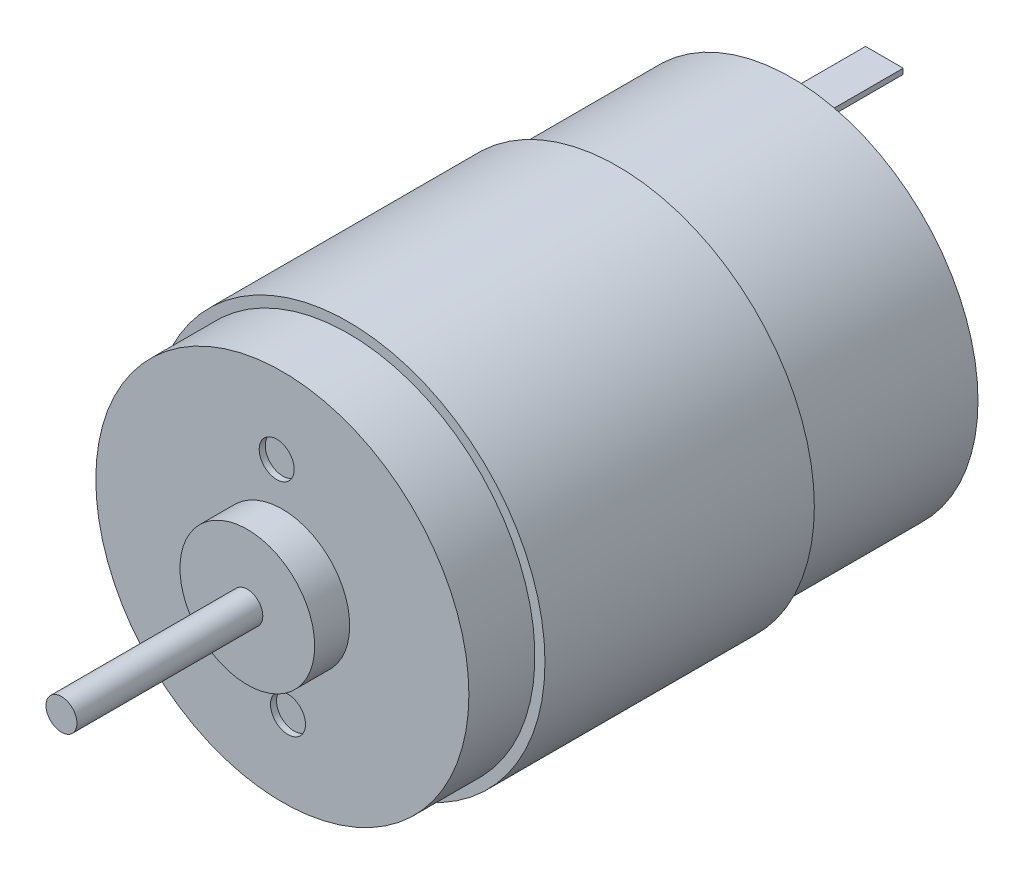
SolidWorks part; units mm, degrees
ref_plane "正面" through (0, 0, 0) normal (0, 0, 1) x (1, 0, 0)
ref_plane "平面" through (0, 0, 0) normal (0, 1, 0) x (1, 0, 0)
ref_plane "右側面" through (0, 0, 0) normal (1, 0, 0) x (0, 0, -1)
sketch "ｽｹｯﾁ1" plane through (0, 0, 0) normal (0, 0, 1) x (1, 0, 0)
  circle A0 centre (0, 0) radius 13.85
  dimension "D1" = 27.7
extrude "ﾎﾞｽ - 押し出し1" add sketch "ｽｹｯﾁ1" along normal blind 37.8
sketch "ｽｹｯﾁ2" plane through (0, 0, 37.8) normal (0, 0, 1) x (1, 0, 0)
  circle A0 centre (0, 0) radius 5
  dimension "D1" = 10
extrude "ﾎﾞｽ - 押し出し2" add sketch "ｽｹｯﾁ2" along normal blind 2.6
sketch "ｽｹｯﾁ3" plane through (0, 0, 40.4) normal (0, 0, 1) x (1, 0, 0)
  circle A0 centre (0, 0) radius 1.15
  dimension "D1" = 2.3
extrude "ﾎﾞｽ - 押し出し3" add sketch "ｽｹｯﾁ3" along normal blind 16.4 from surface at -2.6 starting at face at (5, 0, 37.8)
sketch "ｽｹｯﾁ4" plane through (0, 0, 0) normal (0, 0, -1) x (-1, 0, 0)
  circle A0 centre (0, 0) radius 14.6
  dimension "D1" = 29.2
extrude "ﾎﾞｽ - 押し出し4" add sketch "ｽｹｯﾁ4" along normal blind 20 from offset 32.9 offset against normal yes
sketch "ｽｹｯﾁ5" plane through (0, 0, 0) normal (0, 0, -1) x (-1, 0, 0)
  circle A0 centre (0, 0) radius 5
  point P2 (0, 0)
  dimension "D1" = 10
extrude "ﾎﾞｽ - 押し出し5" add sketch "ｽｹｯﾁ5" along normal blind 2.6
sketch "ｽｹｯﾁ6" plane through (0, 0, 0) normal (0, 0, -1) x (-1, 0, 0)
  line L0 (-7.9588, 0) -> (7.9588, 0) construction
  line L1 (-1.4, 11.7) -> (1.4, 11.7)
  line L2 (-1.4, 11.7) -> (-1.4, 11.3)
  line L3 (-1.4, 11.3) -> (1.4, 11.3)
  line L4 (1.4, 11.7) -> (1.4, 11.3)
  line L5 (-1.4, 11.7) -> (1.4, 11.3) construction
  line L6 (-1.4, 11.3) -> (1.4, 11.7) construction
  line L7 (-1.4, -11.3) -> (1.4, -11.3)
  line L8 (1.4, -11.7) -> (1.4, -11.3)
  line L9 (-1.4, -11.7) -> (1.4, -11.7)
  line L10 (-1.4, -11.7) -> (-1.4, -11.3)
  point P4 (0, 11.5)
  point P5 (0, 0)
  dimension "D1" = 2.8
  dimension "D2" = 0.4
  dimension "D3" = 22.6
extrude "ﾎﾞｽ - 押し出し6" add sketch "ｽｹｯﾁ6" along normal blind 6.9
sketch "ｽｹｯﾁ7" plane through (0, 0, 37.8) normal (0, 0, 1) x (1, 0, 0)
  line L0 (-10.1434, -0.5316) -> (20.731, 1.0865) construction
  line L1 (-0.834, 15.9137) -> (0.869, -16.5818) construction
  line L2 (0, 15.8662) -> (0, -16.6076) construction
  circle A0 centre (-0.4187, 7.989) radius 1.3
  circle A1 centre (0.4187, -7.989) radius 1.3
  point P9 (0, 0)
  dimension "D2" = 2.6
  dimension "D1" = 3
  dimension "D3" = 16
extrude "ｶｯﾄ - 押し出し1" cut sketch "ｽｹｯﾁ7" against normal blind 0.45
